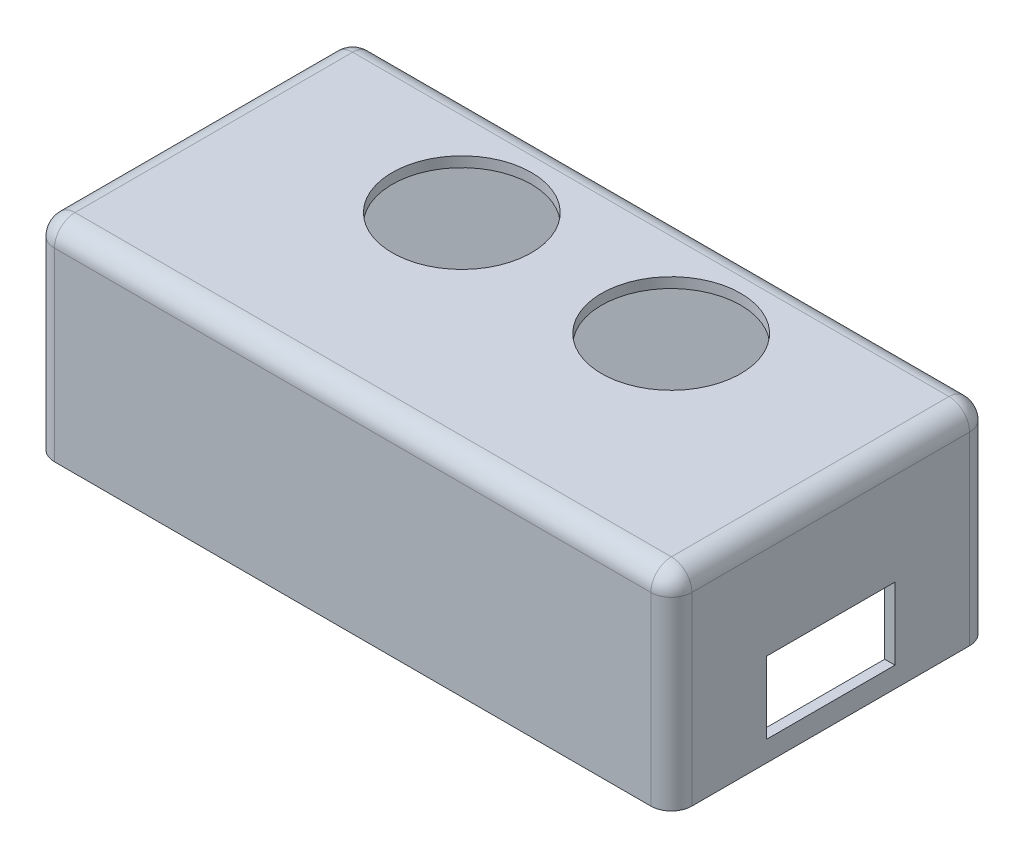
SolidWorks part; units mm, degrees
ref_plane "Front Plane" through (0, 0, 0) normal (0, 0, 1) x (1, 0, 0)
ref_plane "Top Plane" through (0, 0, 0) normal (0, 1, 0) x (1, 0, 0)
ref_plane "Right Plane" through (0, 0, 0) normal (1, 0, 0) x (0, 0, -1)
sketch "Sketch1" plane through (0, 0, 0) normal (0, 1, 0) x (1, 0, 0)
  line L1 (0, 0) -> (-78.74, 0)
  line L2 (0, 0) -> (0, 39.37)
  line L3 (0, 39.37) -> (-78.74, 39.37)
  line L4 (-78.74, 0) -> (-78.74, 39.37)
  dimension "D1" = 78.74
  dimension "D2" = 39.37
extrude "Boss-Extrude1" add sketch "Sketch1" along normal blind 25.4
fillet "Fillet1" radius 2.54 8 edges at (-39.37, 25.4, 0) (-78.74, 25.4, -19.685) (-39.37, 25.4, -39.37) (0, 25.4, -19.685) (-78.74, 12.7, -39.37) (-78.74, 12.7, 0) (0, 12.7, 0) (0, 12.7, -39.37)
shell "Shell1" thickness 1.27
sketch "Sketch2" plane through (0, 24.13, 0) normal (0, -1, 0) x (1, 0, 0)
  line L0 (-52.2986, -26.416) -> (-26.4414, -26.416) construction
  line L1 (-39.37, -26.416) -> (-39.37, -1.27) construction
  line L2 (-76.2, -1.27) -> (-2.54, -1.27) construction
  line L3 (-62.1884, -26.416) -> (-52.2986, -26.416) construction
  line L4 (-62.1884, -16.002) -> (-16.5516, -16.002) construction
  line L5 (-62.1884, -16.002) -> (-62.1884, -36.83) construction
  line L6 (-62.1884, -36.83) -> (-16.5516, -36.83) construction
  line L7 (-16.5516, -16.002) -> (-16.5516, -36.83) construction
  line L8 (-2.54, -38.1) -> (-76.2, -38.1) construction
  line L9 (-39.37, -36.83) -> (-39.37, -38.1) construction
  circle A0 centre (-52.2986, -26.416) radius 7.9629 construction
  circle A1 centre (-26.4414, -26.416) radius 7.9629 construction
  circle A2 centre (-52.2986, -26.416) radius 8.5979
  circle A3 centre (-26.4414, -26.416) radius 8.5979
  dimension "D1" = 15.9258
  dimension "D2" = 41.783
  dimension "D3" = 20.828
  dimension "D4" = 45.6368
  dimension "D5" = 1.27
  dimension "D6" = 0.635
extrude "Cut-Extrude1" cut sketch "Sketch2" against normal through all
sketch "Sketch3" plane through (0, 0, 0) normal (1, 0, 0) x (0, 0, -1)
  line L0 (2.54, 0) -> (36.83, 0) construction
  line L1 (11.7475, 2.54) -> (27.6225, 2.54)
  line L2 (11.7475, 2.54) -> (11.7475, 11.43)
  line L3 (11.7475, 11.43) -> (27.6225, 11.43)
  line L4 (27.6225, 2.54) -> (27.6225, 11.43)
  line L5 (19.685, 11.43) -> (19.685, 25.4) construction
  line L6 (0, 25.4) -> (39.37, 25.4) construction
  dimension "D1" = 2.54
  dimension "D2" = 8.89
  dimension "D3" = 15.875
extrude "Cut-Extrude2" cut sketch "Sketch3" against normal up to surface (1.27 mm away) up to face at (-1.27, 11.43, -19.685)
